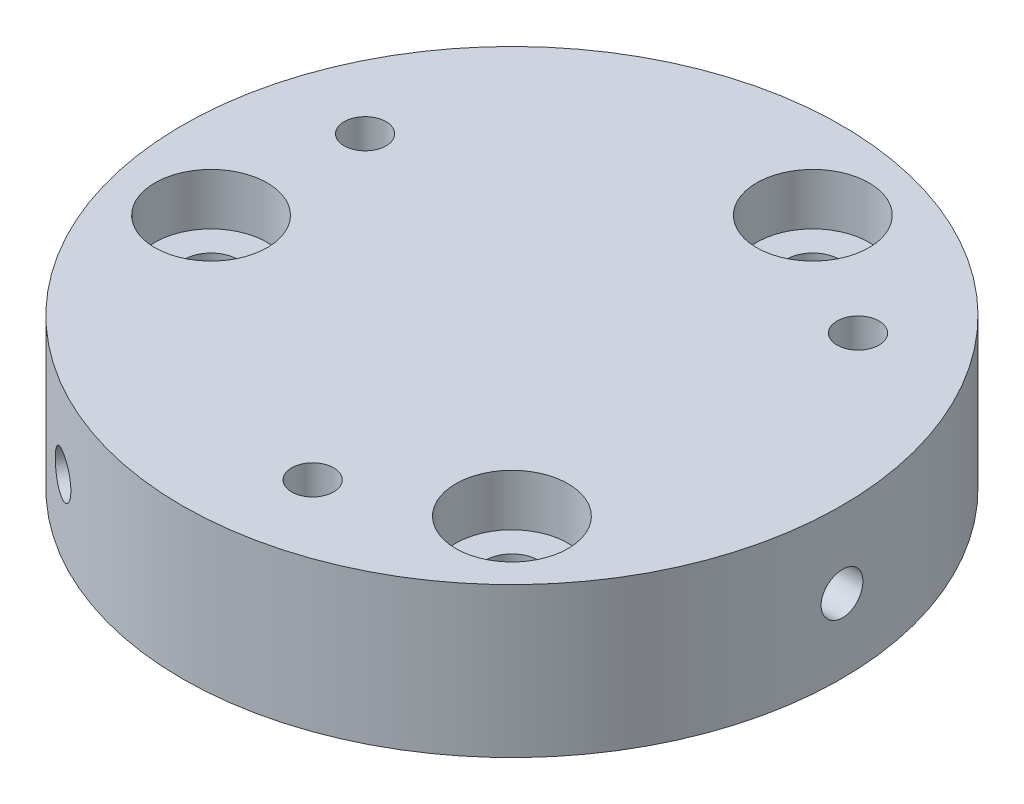
SolidWorks part; units mm, degrees
ref_plane "Front Plane" through (0, 0, 0) normal (0, 0, 1) x (1, 0, 0)
ref_plane "Top Plane" through (0, 0, 0) normal (0, 1, 0) x (1, 0, 0)
ref_plane "Right Plane" through (0, 0, 0) normal (1, 0, 0) x (0, 0, -1)
sketch "Sketch1" plane through (0, 0, 0) normal (0, 1, 0) x (1, 0, 0)
  circle A0 centre (0, 0) radius 13.97
  dimension "D1" = 27.94
extrude "Boss-Extrude1" add sketch "Sketch1" along normal blind 6.35
hole_wizard "CBORE for #2 Socket Head Cap Screw1" positions "Sketch3" profile "Sketch4" counterbore size "#2" standard "ANSI Inch" end condition through all
sketch "Sketch3" plane through (0, 6.35, 0) normal (0, 1, 0) x (1, 0, 0)
  line L3 (0, 0) -> (7.3638, -7.3638)
  point P0 (7.3638, -7.3638)
sketch "Sketch4" plane through (7.3638, 6.35, 7.3638) normal (1, 0, 0) x (0, 0, 1)
  line L0 (0, 0) -> (0, 6.35)
  line L1 (0, 6.35) -> (1.1303, 6.35)
  line L3 (1.1303, 6.35) -> (1.1303, 2.1844)
  line L4 (1.1303, 2.1844) -> (2.3812, 2.1844)
  line L5 (2.3812, 2.1844) -> (2.3812, 0)
  line L7 (2.3812, 0) -> (0, 0)
  line L11 (0, -6.35) -> (0, 107.95) construction
  dimension "Thru Hole Dia." = 2.2606
  dimension "Thru Hole Depth" = 6.35
  dimension "C'Bore Dia." = 4.7625
  dimension "C'Bore Depth" = 2.1844
pattern_circular "CirPattern1" count 3 over 360 about axis through (0, 0, 0) along (0, 1, 0) of "CBORE for #2 Socket Head Cap Screw1"
sketch "Sketch9" plane through (0, 6.35, 0) normal (0, 1, 0) x (1, 0, 0)
  line L0 (0, 0) -> (7.9776, 6.694)
  circle A0 centre (7.9776, 6.694) radius 1.4122
hole_wizard "Tap Drill for #2-56 Tap2" positions "3DSketch1" profile "Sketch10" hole size "#2-56" standard "ANSI Inch"
sketch3d "3DSketch1"
  point P0 (7.9776, 6.35, -6.694)
sketch "Sketch10" plane through (7.9776, 6.35, -6.694) normal (1, 0, 0) x (0, 0, 1)
  line L0 (0, 0) -> (0, 4.5982)
  line L1 (0, 4.5982) -> (0.889, 4.064)
  line L2 (0.889, 4.064) -> (0.889, 0)
  line L5 (0.889, 0) -> (0, 0)
  line L10 (0, 4.5982) -> (-0.889, 4.064) construction
  line L11 (0, -6.35) -> (0, 107.95) construction
  dimension "Hole Dia." = 1.778
  dimension "Hole Depth" = 4.064
  dimension "Drill Angle" = 118
pattern_circular "CirPattern2" count 3 every 120 about axis through (0, 0, 0) along (0, 1, 0) of "Tap Drill for #2-56 Tap2"
ref_plane "Plane1" [suppressed] through (0, 3.175, 0) normal (0, 1, 0) x (1, 0, 0)
sketch "Sketch11" [suppressed] plane through (0, 3.175, 0) normal (0, 1, 0) x (1, 0, 0)
  line L0 (0, 0) -> (-7.135, -12.0105)
  circle A0 centre (0, 0) radius 13.97 construction
ref_plane "Plane2" [suppressed] through (-7.135, 3.175, 12.0105) normal (-0.5107, 0, 0.8597) x (0.8597, 0, 0.5107)
hole_wizard "Tap Drill for #2-56 Tap1" positions "3DSketch3" profile "Sketch15" hole size "#2-56" standard "ANSI Inch"
sketch3d "3DSketch3"
  point P0 (-6.9425, 3.1056, 12.1228)
sketch "Sketch15" plane through (-6.9425, 3.1056, 12.1228) normal (0, 1, 0) x (0.8678, 0, 0.497)
  line L0 (0, 0) -> (0, 7.096)
  line L1 (0, 7.096) -> (0.889, 6.35)
  line L2 (0.889, 6.35) -> (0.889, 0)
  line L5 (0.889, 0) -> (0, 0)
  line L10 (0, 7.096) -> (-0.889, 6.35) construction
  line L11 (0, -6.35) -> (0, 107.95) construction
  dimension "Hole Dia." = 1.778
  dimension "Hole Depth" = 6.35
  dimension "Drill Angle" = 100
pattern_circular "CirPattern3" count 3 every 120 about axis through (0, 6.35, 0) along (0, -1, 0) of "Tap Drill for #2-56 Tap1"
